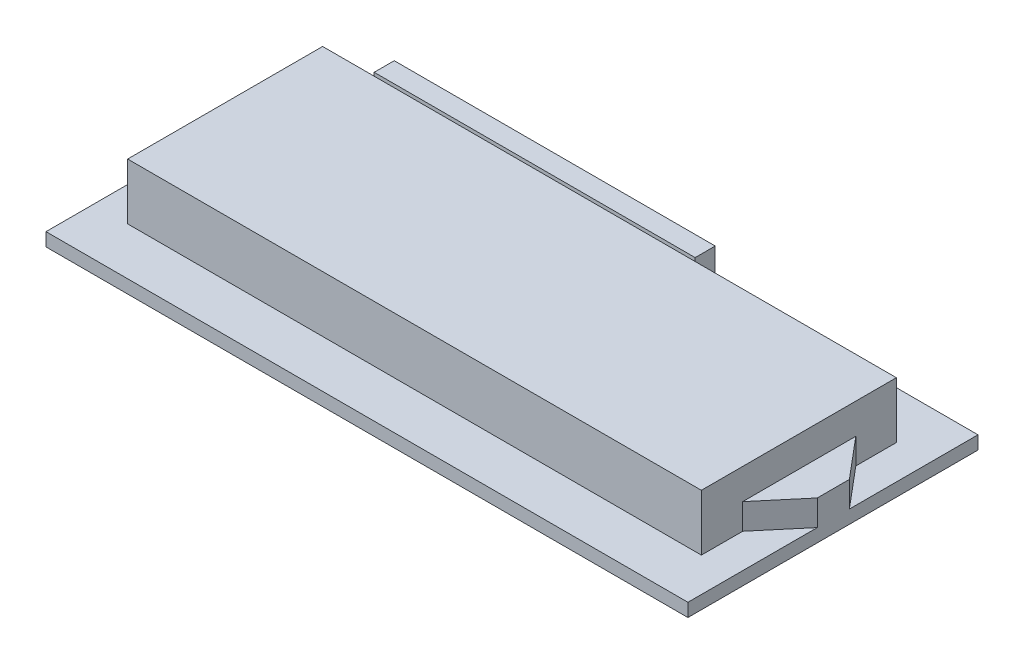
SolidWorks part; units mm, degrees
ref_plane "Front Plane" through (0, 0, 0) normal (0, 0, 1) x (1, 0, 0)
ref_plane "Top Plane" through (0, 0, 0) normal (0, 1, 0) x (1, 0, 0)
ref_plane "Right Plane" through (0, 0, 0) normal (1, 0, 0) x (0, 0, -1)
sketch "Sketch1" plane through (0, 0, 0) normal (0, 1, 0) x (1, 0, 0)
  line L1 (0, 0) -> (80, 0)
  line L2 (0, 0) -> (0, 36.15)
  line L3 (0, 36.15) -> (80, 36.15)
  line L5 (4.25, 5.925) -> (75.75, 5.925)
  line L6 (4.25, 5.925) -> (4.25, 30.225)
  line L7 (4.25, 30.225) -> (75.75, 30.225)
  line L9 (7.25, 36.15) -> (47.25, 36.15)
  line L10 (7.25, 36.15) -> (7.25, 33.65)
  line L11 (7.25, 33.65) -> (47.25, 33.65)
  line L12 (47.25, 36.15) -> (47.25, 33.65)
  line L13 (75.75, 25.1707) -> (80, 20.1207)
  line L14 (80, 20.1207) -> (80, 16.1207)
  line L15 (80, 16.1207) -> (75.75, 11.0707)
  line L17 (75.75, 25.1707) -> (75.75, 11.0707)
  line L18 (75.75, 30.225) -> (75.75, 25.1707)
  line L19 (75.75, 11.0707) -> (75.75, 5.925)
  line L20 (80, 36.15) -> (80, 20.1207)
  line L21 (80, 16.1207) -> (80, 0)
  dimension "D1" = 36.15
  dimension "D2" = 80
  dimension "D3" = 71.5
  dimension "D4" = 24.3
  dimension "D5" = 40
  dimension "D6" = 2.5
  dimension "D7" = 5.925
  dimension "D8" = 14.1
  dimension "D9" = 4
  dimension "D10" = 4.25
  dimension "D11" = 3
sketch "Sketch3" plane through (0, 0, 0) normal (0, 1, 0) x (1, 0, 0)
  line L0 (0, 0) -> (0, 36.15) construction
  line L1 (0, 0) -> (80, 0) construction
  line L2 (80, 16.1207) -> (80, 0) construction
  line L3 (80, 20.1207) -> (80, 16.1207) construction
  line L4 (80, 36.15) -> (80, 20.1207) construction
  line L5 (0, 36.15) -> (80, 36.15) construction
  line L6 (0, 0) -> (0, 36.15)
  line L7 (0, 0) -> (80, 0)
  line L8 (80, 16.1207) -> (80, 0)
  line L9 (80, 20.1207) -> (80, 16.1207)
  line L10 (80, 36.15) -> (80, 20.1207)
  line L11 (0, 36.15) -> (80, 36.15)
extrude "Boss-Extrude2" add sketch "Sketch3" against normal blind 1.65
sketch "Sketch5" plane through (0, 0, 0) normal (0, 1, 0) x (1, 0, 0)
  line L0 (75.75, 11.0707) -> (75.75, 5.925) construction
  line L1 (75.75, 30.225) -> (75.75, 25.1707) construction
  line L2 (75.75, 25.1707) -> (75.75, 11.0707) construction
  line L3 (4.25, 5.925) -> (75.75, 5.925) construction
  line L4 (4.25, 5.925) -> (4.25, 30.225) construction
  line L5 (4.25, 30.225) -> (75.75, 30.225) construction
  line L6 (75.75, 11.0707) -> (75.75, 5.925)
  line L7 (75.75, 30.225) -> (75.75, 25.1707)
  line L8 (75.75, 25.1707) -> (75.75, 11.0707)
  line L9 (4.25, 5.925) -> (75.75, 5.925)
  line L10 (4.25, 5.925) -> (4.25, 30.225)
  line L11 (4.25, 30.225) -> (75.75, 30.225)
extrude "Boss-Extrude3" add sketch "Sketch5" along normal blind 7
sketch "Sketch6" plane through (0, 0, 0) normal (0, 1, 0) x (1, 0, 0)
  line L0 (80, 20.1207) -> (80, 16.1207) construction
  line L1 (80, 16.1207) -> (75.75, 11.0707) construction
  line L2 (75.75, 25.1707) -> (75.75, 11.0707) construction
  line L3 (75.75, 25.1707) -> (80, 20.1207) construction
  line L4 (80, 20.1207) -> (80, 16.1207)
  line L5 (80, 16.1207) -> (75.75, 11.0707)
  line L6 (75.75, 25.1707) -> (75.75, 11.0707)
  line L7 (75.75, 25.1707) -> (80, 20.1207)
extrude "Boss-Extrude4" add sketch "Sketch6" along normal blind 3.2
sketch "Sketch7" plane through (0, 0, 0) normal (0, 1, 0) x (1, 0, 0)
  line L0 (7.25, 33.65) -> (47.25, 33.65) construction
  line L1 (7.25, 36.15) -> (7.25, 33.65) construction
  line L2 (47.25, 36.15) -> (47.25, 33.65) construction
  line L3 (7.25, 33.65) -> (47.25, 33.65)
  line L4 (7.25, 36.15) -> (7.25, 33.65)
  line L5 (47.25, 36.15) -> (47.25, 33.65)
  line L6 (7.25, 36.15) -> (47.25, 36.15)
extrude "Boss-Extrude5" add sketch "Sketch7" along normal blind 4
sketch "Sketch8" plane through (0, -1.65, 0) normal (0, -1, 0) x (1, 0, 0)
  line L2 (7.25, -36.15) -> (7.25, -33.65) construction
  line L5 (47.25, -36.15) -> (7.25, -36.15) construction
  line L8 (47.25, -36.15) -> (7.25, -36.15)
  line L10 (47.25, -36.15) -> (7.25, -36.15)
  line L11 (47.25, -36.15) -> (47.25, -17)
  line L12 (47.25, -17) -> (7.25, -17)
  line L13 (7.25, -36.15) -> (7.25, -17)
  point P0 (47.25, -36.15)
  line M4 (0, -36.15) -> (80, -36.15)
  dimension "D1" = 19.15
  dimension "D2" = 40
extrude "Boss-Extrude6" add sketch "Sketch8" along normal blind 11.1 contours L13 L11 L12 M4
sketch "Sketch9" plane through (47.25, 0, 0) normal (1, 0, 0) x (0, 0, -1)
  line L2 (28.975, -12.75) -> (28.975, -10.25)
  line L3 (28.975, -10.25) -> (24.175, -10.25)
  line L4 (24.175, -10.25) -> (24.175, -12.75)
  line L6 (24.175, -12.75) -> (28.975, -12.75)
  line L7 (36.15, -12.75) -> (17, -12.75) construction
  line L8 (36.15, -12.75) -> (36.15, -1.65) construction
  line L9 (17, -12.75) -> (17, -1.65) construction
  line L10 (36.15, -1.65) -> (17, -1.65) construction
  dimension "D1" = 2.5
  dimension "D2" = 4.8
  dimension "D3" = 7.175
extrude "Boss-Extrude7" add sketch "Sketch9" along normal blind 6
